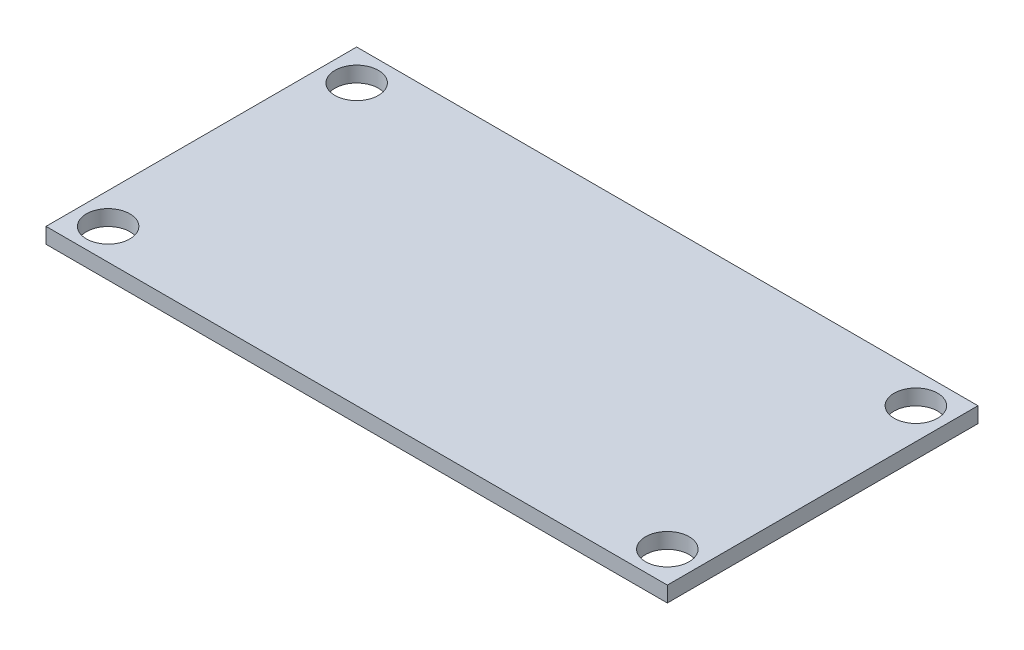
SolidWorks part; units mm, degrees
ref_plane "Front Plane" through (0, 0, 0) normal (0, 0, 1) x (1, 0, 0)
ref_plane "Top Plane" through (0, 0, 0) normal (0, 1, 0) x (1, 0, 0)
ref_plane "Right Plane" through (0, 0, 0) normal (1, 0, 0) x (0, 0, -1)
sketch "Sketch1" plane through (0, 0, 0) normal (0, 1, 0) x (1, 0, 0)
  line L1 (0, 0) -> (40, 0)
  line L2 (0, 0) -> (0, 20)
  line L3 (0, 20) -> (40, 20)
  line L4 (40, 0) -> (40, 20)
  dimension "D1" = 40
  dimension "D2" = 20
extrude "Boss-Extrude1" add sketch "Sketch1" along normal blind 1
sketch "Sketch2" plane through (0, 1, 0) normal (0, 1, 0) x (1, 0, 0)
  line L0 (2, 10) -> (0, 10) construction
  line L1 (2, 18) -> (38, 18) construction
  line L2 (2, 18) -> (2, 2) construction
  line L3 (2, 2) -> (38, 2) construction
  line L4 (38, 18) -> (38, 2) construction
  line L5 (0, 20) -> (0, 0) construction
  line L6 (20, 18) -> (20, 20) construction
  line L7 (40, 20) -> (0, 20) construction
  line L8 (20, 0) -> (20, 2) construction
  line L9 (0, 0) -> (40, 0) construction
  line L10 (38, 10) -> (40, 10) construction
  line L11 (40, 0) -> (40, 20) construction
  circle A0 centre (2, 18) radius 1.4
  circle A1 centre (38, 18) radius 1.4
  circle A2 centre (38, 2) radius 1.4
  circle A3 centre (2, 2) radius 1.4
  dimension "D3" = 2.8
  dimension "D1" = 2
  dimension "D2" = 2
extrude "Cut-Extrude1" cut sketch "Sketch2" against normal through all
